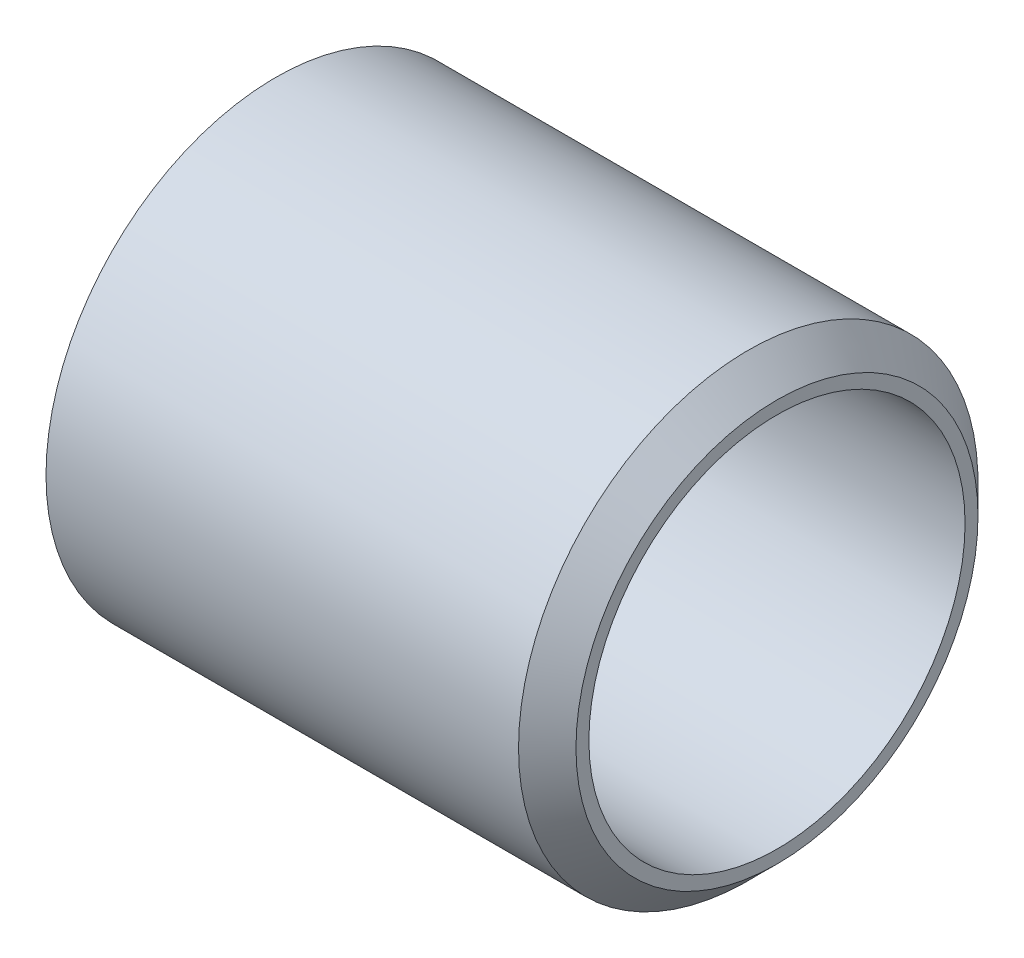
SolidWorks part; units mm, degrees
ref_plane "Plane1" through (0, 0, 0) normal (0, 0, 1) x (1, 0, 0)
ref_plane "Plane2" through (0, 0, 0) normal (0, 1, 0) x (1, 0, 0)
ref_plane "Plane3" through (0, 0, 0) normal (1, 0, 0) x (0, 0, -1)
sketch "Sketch1" plane through (0, 0, 0) normal (0, 0, 1) x (1, 0, 0)
  line L0 (0, 0) -> (76.2, 0) construction
  line L1 (0, 31.7691) -> (0, 34.925)
  line L4 (0, 34.925) -> (71.8344, 34.925)
  line L5 (71.8344, 34.925) -> (76.2, 30.5594)
  line L6 (76.2, 30.5594) -> (76.2, 28.594)
  line L7 (76.2, 28.594) -> (3.175, 28.5941)
  line L8 (71.8344, -34.925) -> (76.2, -30.5594) construction
  line L9 (76.2, -28.594) -> (0, -28.5941) construction
  line L10 (0, -34.925) -> (71.8344, -34.925) construction
  arc A1 (0, 31.7691) -> (3.175, 28.5941) centre (3.175, 31.7691) ccw
  point P20 (0, 28.5941)
  dimension "Head_radius" = 3.175
  dimension "Hole_dia" = 57.1881
  dimension "Body_dia" = 69.85
  dimension "Body_len" = 76.2
  dimension "D1" = 61.1187
  dimension "D2" = 45
revolve "BaseBody" add sketch "Sketch1" angle 360 about L0
equation "\"D1@Sketch1\" = \"Body_dia@Sketch1\" * .875"
